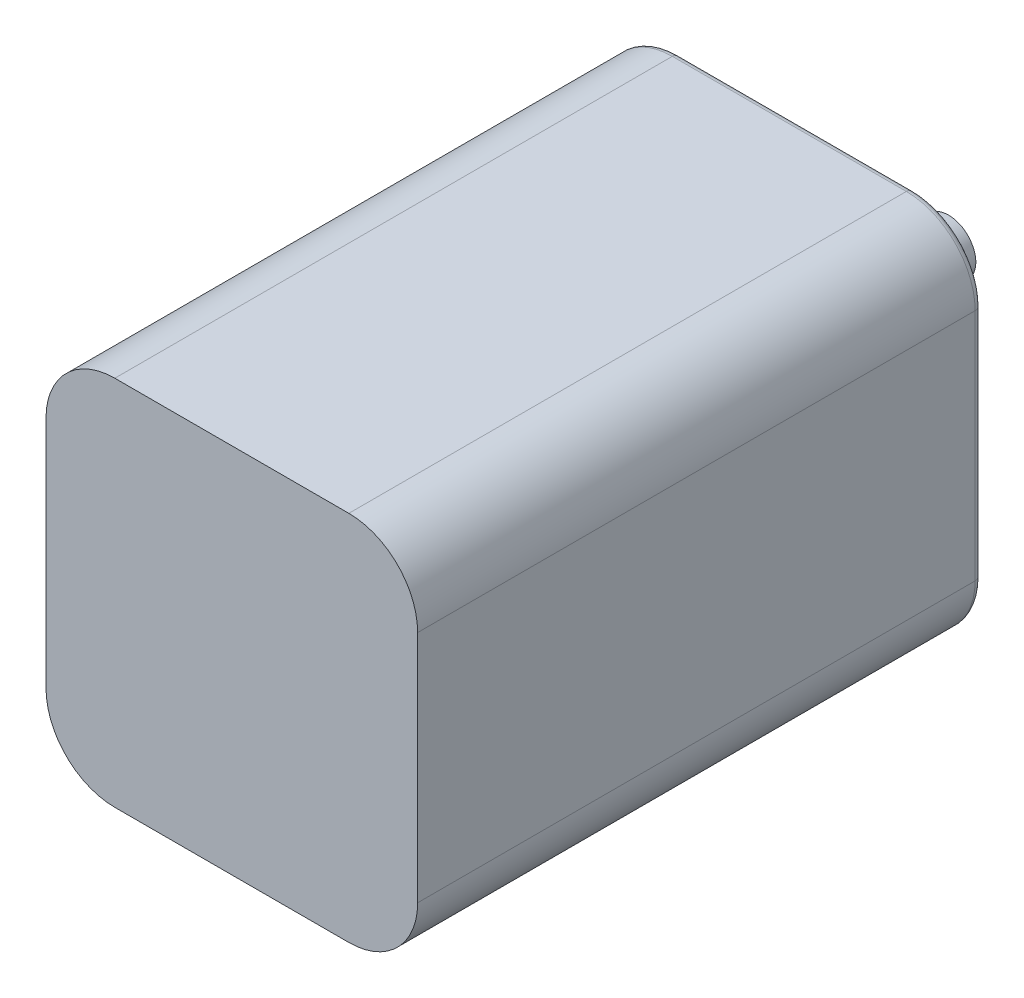
SolidWorks part; units mm, degrees
ref_plane "Front Plane" through (0, 0, 0) normal (0, 0, 1) x (1, 0, 0)
ref_plane "Top Plane" through (0, 0, 0) normal (0, 1, 0) x (1, 0, 0)
ref_plane "Right Plane" through (0, 0, 0) normal (1, 0, 0) x (0, 0, -1)
sketch "Sketch1" plane through (0, 0, 0) normal (0, 0, 1) x (1, 0, 0)
  line L1 (-34.29, -34.29) -> (34.29, -34.29)
  line L2 (-34.29, -34.29) -> (-34.29, 34.29)
  line L3 (-34.29, 34.29) -> (34.29, 34.29)
  line L4 (34.29, -34.29) -> (34.29, 34.29)
  line L5 (-34.29, -34.29) -> (34.29, 34.29) construction
  line L6 (-34.29, 34.29) -> (34.29, -34.29) construction
  point P0 (0, 0)
  dimension "D1" = 68.58
  dimension "D2" = 68.58
extrude "Boss-Extrude2" add sketch "Sketch1" along normal blind 104.14
fillet "Side Fillets" radius 12.7 4 edges at (-34.29, 34.29, 52.07) (34.29, 34.29, 52.07) (34.29, -34.29, 52.07) (-34.29, -34.29, 52.07)
sketch "Sketch8" plane through (0, 0, 0) normal (0, 0, -1) x (-1, 0, 0)
  line L8 (30.48, -21.59) -> (30.48, 21.59)
  line L9 (21.59, 30.48) -> (-21.59, 30.48)
  line L10 (-30.48, 21.59) -> (-30.48, -21.59)
  line L11 (-21.59, -30.48) -> (21.59, -30.48)
  line L12 (30.48, -21.59) -> (30.48, 21.59)
  line L13 (21.59, 30.48) -> (-21.59, 30.48)
  line L14 (-30.48, 21.59) -> (-30.48, -21.59)
  line L15 (-21.59, -30.48) -> (21.59, -30.48)
  arc A8 (30.48, 21.59) -> (21.59, 30.48) centre (21.59, 21.59) ccw
  arc A9 (-21.59, 30.48) -> (-30.48, 21.59) centre (-21.59, 21.59) ccw
  arc A10 (-30.48, -21.59) -> (-21.59, -30.48) centre (-21.59, -21.59) ccw
  arc A11 (21.59, -30.48) -> (30.48, -21.59) centre (21.59, -21.59) ccw
  arc A12 (30.48, 21.59) -> (21.59, 30.48) centre (21.59, 21.59) ccw
  arc A13 (-21.59, 30.48) -> (-30.48, 21.59) centre (-21.59, 21.59) ccw
  arc A14 (-30.48, -21.59) -> (-21.59, -30.48) centre (-21.59, -21.59) ccw
  arc A15 (21.59, -30.48) -> (30.48, -21.59) centre (21.59, -21.59) ccw
  dimension "D1" = 3.81
extrude "Top Cut" cut sketch "Sketch8" against normal blind 5.08
fillet "Top Face Fillet" radius 1.27 16 edges at (-30.5703, -30.5703, 0) (0, -34.29, 0) (30.5703, -30.5703, 0) (34.29, 0, 0) (30.5703, 30.5703, 0) (0, 34.29, 0) (-30.5703, 30.5703, 0) (-34.29, 0, 0) (-30.48, 0, 0) (-27.8762, 27.8762, 0) (0, 30.48, 0) (27.8762, 27.8762, 0) (30.48, 0, 0) (27.8762, -27.8762, 0) (0, -30.48, 0) (-27.8762, -27.8762, 0)
sketch "Sketch-TERMINALS" plane through (0, 0, 5.08) normal (0, 0, -1) x (-1, 0, 0)
  line L0 (-17.9605, 17.9605) -> (0, 0) construction
  circle A0 centre (0, 0) radius 6.35
  circle A1 centre (-17.9605, 17.9605) radius 6.35
  dimension "D1" = 12.7
  dimension "D2" = 25.4
  dimension "D3" = 45
extrude "Terminals" add sketch "Sketch-TERMINALS" along normal blind 15.24 draft 5
